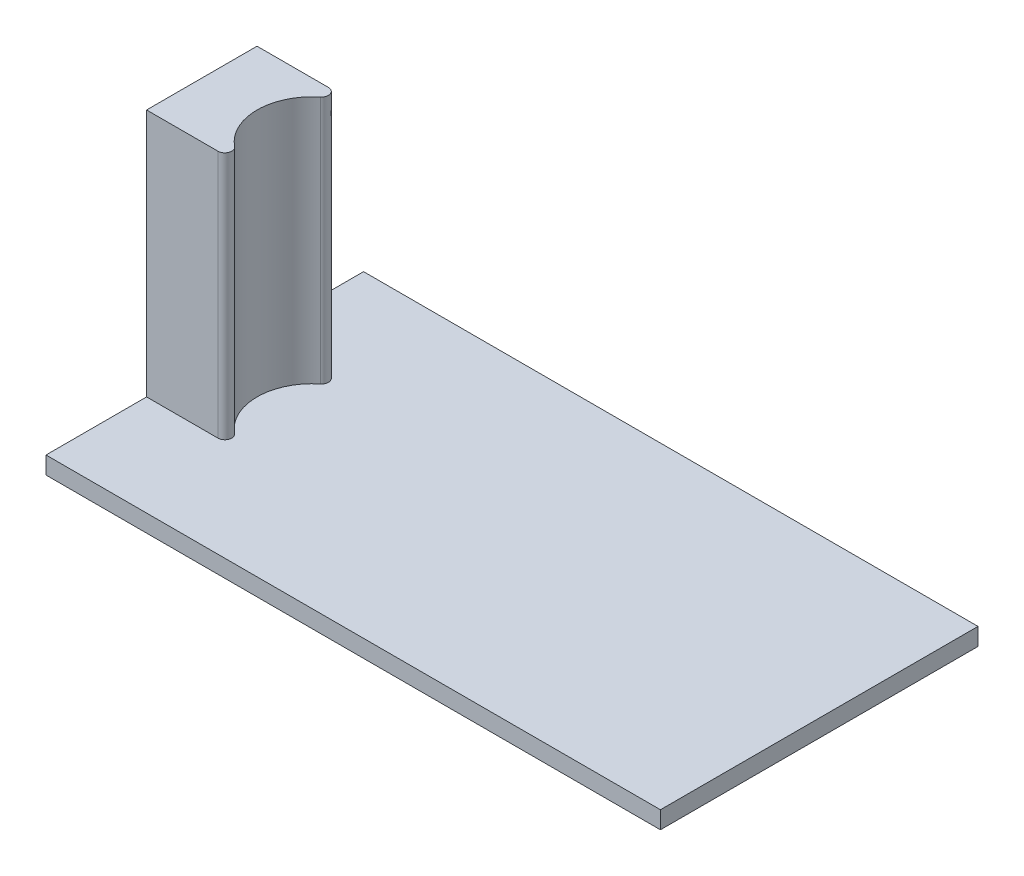
SolidWorks part; units mm, degrees
material "ABS"
ref_plane "Front Plane" through (0, 0, 0) normal (0, 0, 1) x (1, 0, 0)
ref_plane "Top Plane" through (0, 0, 0) normal (0, 1, 0) x (1, 0, 0)
ref_plane "Right Plane" through (0, 0, 0) normal (1, 0, 0) x (0, 0, -1)
sketch "Sketch3" plane through (0, 0, 0) normal (0, 1, 0) x (1, 0, 0)
  line L0 (-27.7812, 0) -> (-27.7812, 25.4)
  line L1 (-27.7812, 25.4) -> (-11.3615, 25.4)
  line L3 (-27.7812, 0) -> (-11.3615, 0)
  arc A0 (-11.3615, 0) -> (-10.3637, 2.8222) centre (-11.3615, 1.5875) ccw
  arc A1 (-11.3615, 25.4) -> (-10.3637, 22.5778) centre (-11.3615, 23.8125) cw
  arc A2 (-10.3637, 22.5778) -> (-10.3637, 2.8222) centre (-2.3813, 12.7) ccw
extrude "Boss-Extrude1" add sketch "Sketch3" along normal blind 57.15
sketch "Sketch4" plane through (0, 0, 0) normal (0, -1, 0) x (1, 0, 0)
  line L0 (-27.7812, 0) -> (-27.7812, -25.4) construction
  line L1 (-27.7813, 23.13) -> (-6.3897, 23.13)
  line L2 (-27.7813, 23.13) -> (-27.7812, -49.9)
  line L3 (-27.7812, -49.9) -> (-6.3897, -49.9)
  line L4 (-6.3897, 23.13) -> (-6.3897, -49.9)
  line L5 (-27.7812, -25.4) -> (-11.3615, -25.4) construction
  dimension "D1" = 0
  dimension "D2" = 73.03
  dimension "D3" = 24.5
extrude "Boss-Extrude2" add sketch "Sketch4" along normal blind 4
sketch "Sketch5" plane through (0, -4, 0) normal (0, -1, 0) x (-1, 0, 0)
  line L0 (27.7812, 49.9) -> (6.3897, 49.9) construction
  line L1 (6.3897, -23.13) -> (-113.5187, -23.13)
  line L2 (6.3897, -23.13) -> (6.3897, 49.9)
  line L3 (6.3897, 49.9) -> (-113.5187, 49.9)
  line L4 (-113.5187, -23.13) -> (-113.5187, 49.9)
  dimension "D1" = 0
extrude "Boss-Extrude3" add sketch "Sketch5" against normal blind 4
